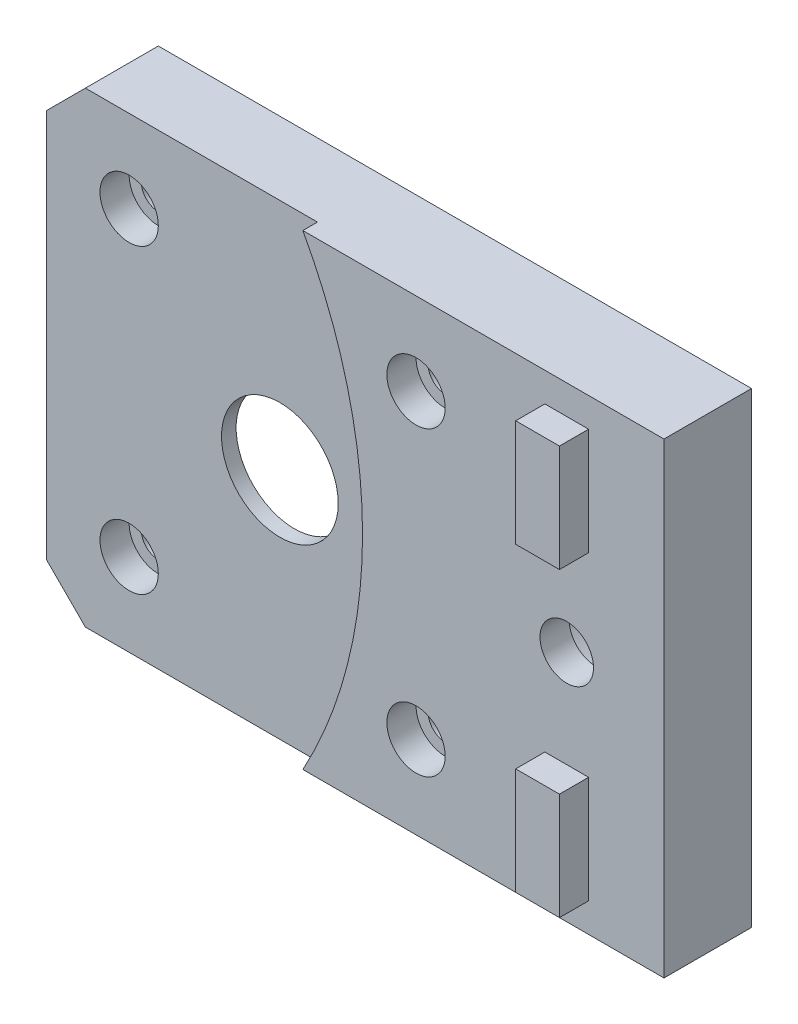
SolidWorks part; units mm, degrees
ref_plane "Front Plane" through (0, 0, 0) normal (0, 0, 1) x (1, 0, 0)
ref_plane "Top Plane" through (0, 0, 0) normal (0, 1, 0) x (1, 0, 0)
ref_plane "Right Plane" through (0, 0, 0) normal (1, 0, 0) x (0, 0, -1)
sketch "Sketch1" plane through (0, 0, 0) normal (0, 0, 1) x (1, 0, 0)
  line L1 (-21, -21) -> (21, -21)
  line L2 (-21, -21) -> (-21, 21)
  line L3 (-21, 21) -> (21, 21)
  line L4 (21, -21) -> (21, 21)
  line L5 (-21, -21) -> (21, 21) construction
  line L6 (-21, 21) -> (21, -21) construction
  line L7 (21, 21) -> (41, 21)
  line L8 (21, 21) -> (21, -21)
  line L9 (21, -21) -> (41, -21)
  line L10 (41, 21) -> (41, -21)
  point P0 (0, 0)
  dimension "D1" = 42
  dimension "D2" = 42
  dimension "D3" = 20
extrude "Boss-Extrude1" add sketch "Sketch1" along normal blind 6 contours L10 L7 L4 L9 | L1 L4 L3 L2
sketch "Sketch2" plane through (0, 0, 0) normal (0, 0, 1) x (1, 0, 0)
  circle A0 centre (0, 0) radius 11.25
  dimension "D1" = 22.5
extrude "Cut-Extrude1" cut sketch "Sketch2" along normal blind 3
sketch "Sketch3" plane through (0, 0, 0) normal (0, 0, 1) x (1, 0, 0)
  line L1 (21, -21) -> (-21, -21)
  line L2 (21, -21) -> (21, 21)
  line L3 (21, 21) -> (-21, 21)
  line L4 (-21, -21) -> (-21, 21)
  line L5 (21, -21) -> (-21, 21) construction
  line L6 (21, 21) -> (-21, -21) construction
  circle A0 centre (-15.4998, 15.4998) radius 1.75
  circle A1 centre (0, 0) radius 6
  circle A2 centre (15.4998, 15.4998) radius 1.75
  circle A3 centre (15.4998, -15.4998) radius 1.75
  circle A4 centre (-15.4998, -15.4998) radius 1.75
  point P0 (0, 0)
  dimension "D1" = 3.5
  dimension "D2" = 3.5
  dimension "D3" = 3.5
  dimension "D4" = 3.5
  dimension "D5" = 12
  dimension "D6" = 21.92
  dimension "D7" = 21.92
  dimension "D8" = 21.92
  dimension "D9" = 21.92
extrude "Cut-Extrude2" cut sketch "Sketch3" along normal through all both and the other way through all contours A2 | A1 | A0 | A4 | A3
sketch "Sketch4" plane through (0, 0, 6) normal (0, 0, 1) x (1, 0, 0)
  circle A0 centre (15.4998, 15.4998) radius 1.75 construction
  circle A1 centre (-15.4998, 15.4998) radius 1.75 construction
  circle A2 centre (15.4998, -15.4998) radius 1.75 construction
  circle A3 centre (-15.4998, -15.4998) radius 1.75 construction
  circle A4 centre (15.4998, 15.4998) radius 1.75
  circle A5 centre (-15.4998, 15.4998) radius 1.75
  circle A6 centre (15.4998, -15.4998) radius 1.75
  circle A7 centre (-15.4998, -15.4998) radius 1.75
  circle A8 centre (-15.4998, -15.4998) radius 3
  circle A9 centre (-15.4998, 15.4998) radius 3
  circle A10 centre (15.4998, 15.4998) radius 3
  circle A11 centre (15.4998, -15.4998) radius 3
  dimension "D1" = 6
  dimension "D2" = 6
  dimension "D3" = 6
  dimension "D4" = 6
extrude "Cut-Extrude3" cut sketch "Sketch4" against normal blind 3
sketch "Sketch5" plane through (0, 0, 6) normal (0, 0, 1) x (1, 0, 0)
  line L0 (-21, 21) -> (41, 21) construction
  line L1 (33.25, -21) -> (28.75, -21)
  line L2 (33.25, -21) -> (33.25, 21)
  line L3 (33.25, 21) -> (28.75, 21)
  line L4 (28.75, -21) -> (28.75, 21)
  line L5 (33.25, -21) -> (28.75, 21) construction
  line L6 (33.25, 21) -> (28.75, -21) construction
  line L7 (41, 21) -> (41, -21) construction
  point P0 (31, 0)
  dimension "D1" = 10
  dimension "D2" = 4.5
extrude "Boss-Extrude2" add sketch "Sketch5" along normal blind 3
chamfer "Chamfer1" distance 3 angle 45 2 edges at (-21, 21, 3) (-21, -21, 3)
sketch "Sketch6" plane through (0, 0, 0) normal (0, 0, -1) x (-1, 0, 0)
  line L0 (-41, 21) -> (-41, -21) construction
  circle A0 centre (-31, 0) radius 2.75
  dimension "D1" = 5.5
  dimension "D2" = 10
extrude "Cut-Extrude4" cut sketch "Sketch6" against normal through all both and the other way through all
sketch "Sketch7" plane through (0, 0, 6) normal (0, 0, 1) x (1, 0, 0)
  line L1 (35.7282, -10) -> (26.2718, -10)
  line L2 (35.7282, -10) -> (35.7282, 10)
  line L3 (35.7282, 10) -> (26.2718, 10)
  line L4 (26.2718, -10) -> (26.2718, 10)
  line L5 (35.7282, -10) -> (26.2718, 10) construction
  line L6 (35.7282, 10) -> (26.2718, -10) construction
  circle A0 centre (31, 0) radius 2.75 construction
  circle A1 centre (31, 0) radius 2.75
  dimension "D1" = 20
extrude "Cut-Extrude5" cut sketch "Sketch7" along normal through all
sketch "Sketch8" plane through (0, 0, 0) normal (0, 0, -1) x (-1, 0, 0)
  line L0 (-21, -21) -> (-21, 21)
  line L1 (24, -24) -> (-41, -24)
  line L2 (24, -24) -> (24, 24)
  line L3 (24, 24) -> (-41, 24)
  line L4 (-41, -24) -> (-41, 24)
  line L6 (21, -18) -> (21, 18)
  line L7 (21, 18) -> (18, 21)
  line L8 (18, 21) -> (-41, 21)
  line L9 (-41, 21) -> (-41, -21)
  line L10 (-41, -21) -> (18, -21)
  line L11 (18, -21) -> (21, -18)
  line L12 (21, -18) -> (21, 18)
  line L13 (21, 18) -> (18, 21)
  line L14 (18, 21) -> (-41, 21)
  line L15 (-41, 21) -> (-41, -21)
  line L16 (-41, -21) -> (18, -21)
  line L17 (18, -21) -> (21, -18)
  line L18 (-21, 21) -> (-41, 21)
  line L19 (-21, 21) -> (-21, -21)
  line L20 (-21, -21) -> (-41, -21)
  line L21 (-41, 21) -> (-41, -21)
  line L22 (-41, -21) -> (-21, -21)
  line L23 (-41, -21) -> (-41, 21)
  line L24 (-41, 21) -> (-21, 21)
  line L25 (-21, -21) -> (-21, 21)
  circle A0 centre (-31, 0) radius 2.75 construction
  circle A1 centre (-31, 0) radius 2.75
  circle A2 centre (-31, 0) radius 7
  line M18 (21, -18) -> (21, 18)
  line M19 (21, 18) -> (18, 21)
  line M20 (18, 21) -> (-41, 21)
  line M21 (-41, 21) -> (-41, -21)
  line M22 (-41, -21) -> (18, -21)
  line M23 (18, -21) -> (21, -18)
  dimension "D6" = 14
  dimension "D2" = 3
  dimension "D3" = 3
  dimension "D4" = 3
  dimension "D5" = 20
  dimension "D1" = 0
extrude "Boss-Extrude4" add sketch "Sketch8" along normal blind 3 and the other way blind 6 contours L4 L1 L2 L3 M20 M19 M18 M23 M22 | L0 A2 M22 M20 M21
chamfer "Chamfer2" distance 4 angle 45 2 edges at (-24, -24, 1.5) (-24, 24, 1.5)
sketch "Sketch9" plane through (0, 0, 6) normal (0, 0, 1) x (1, 0, 0)
  circle A0 centre (-40, 0) radius 50
  dimension "D2" = 100
  dimension "D1" = 40
extrude "Cut-Extrude7" cut sketch "Sketch9" against normal blind 1.5 contours A0
sketch "Sketch10" plane through (0, 0, 3) normal (0, 0, 1) x (1, 0, 0)
  circle A0 centre (-15.4998, 15.4998) radius 3 construction
  circle A1 centre (-15.4998, -15.4998) radius 3 construction
  circle A2 centre (-15.4998, 15.4998) radius 3
  circle A3 centre (-15.4998, -15.4998) radius 3
extrude "Cut-Extrude8" cut sketch "Sketch10" against normal blind 1.5
sketch "Sketch11" plane through (0, 0, 0) normal (0, 0, -1) x (-1, 0, 0)
  circle A1 centre (-31, 0) radius 7
  circle A2 centre (-31, 0) radius 7
  dimension "D1" = 0
extrude "Cut-Extrude9" cut sketch "Sketch11" against normal blind 3
